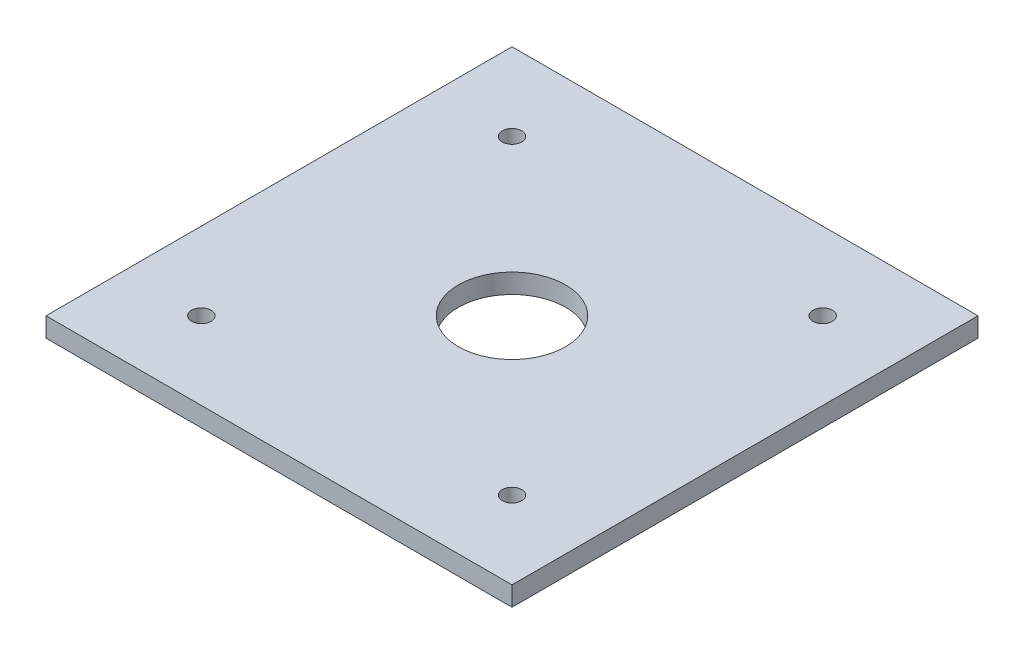
SolidWorks part; units mm, degrees
ref_plane "Front Plane" through (0, 0, 0) normal (0, 0, 1) x (1, 0, 0)
ref_plane "Top Plane" through (0, 0, 0) normal (0, 1, 0) x (1, 0, 0)
ref_plane "Right Plane" through (0, 0, 0) normal (1, 0, 0) x (0, 0, -1)
sketch "Sketch1" plane through (0, 0, 0) normal (0, 1, 0) x (1, 0, 0)
  line L1 (-76.2, 76.2) -> (76.2, 76.2)
  line L2 (-76.2, 76.2) -> (-76.2, -76.2)
  line L3 (-76.2, -76.2) -> (76.2, -76.2)
  line L4 (76.2, 76.2) -> (76.2, -76.2)
  line L5 (-76.2, 76.2) -> (76.2, -76.2) construction
  line L6 (-76.2, -76.2) -> (76.2, 76.2) construction
  circle A0 centre (0, 0) radius 17.526
  point P0 (0, 0)
  dimension "D2" = 35.052
  dimension "D1" = 152.4
extrude "Base" add sketch "Sketch1" along normal blind 6.35
hole_wizard "1/4 (0.25) Diameter Hole1" positions "Sketch2" profile "Sketch3" hole size "1/4" standard "ANSI Inch" end condition through all
sketch "Sketch2" plane through (0, 6.35, 0) normal (0, 1, 0) x (1, 0, 0)
  line L0 (-76.2, -76.2) -> (76.2, -76.2) construction
  line L1 (76.2, -76.2) -> (76.2, 76.2) construction
  point P0 (50.8, -50.8)
  dimension "D1" = 25.4
  dimension "D2" = 25.4
sketch "Sketch3" plane through (50.8, 6.35, 50.8) normal (1, 0, 0) x (0, 0, 1)
  line L0 (0, 0) -> (0, 6.35)
  line L1 (0, 6.35) -> (3.175, 6.35)
  line L2 (3.175, 6.35) -> (3.175, 0)
  line L5 (3.175, 0) -> (0, 0)
  line L11 (0, -6.35) -> (0, 107.95) construction
  dimension "Thru Hole Dia." = 6.35
  dimension "Thru Hole Depth" = 6.35
pattern_circular "CirPattern1" count 4 over 360 about axis through (0, 0, 0) along (0, 1, 0) of "1/4 (0.25) Diameter Hole1"
